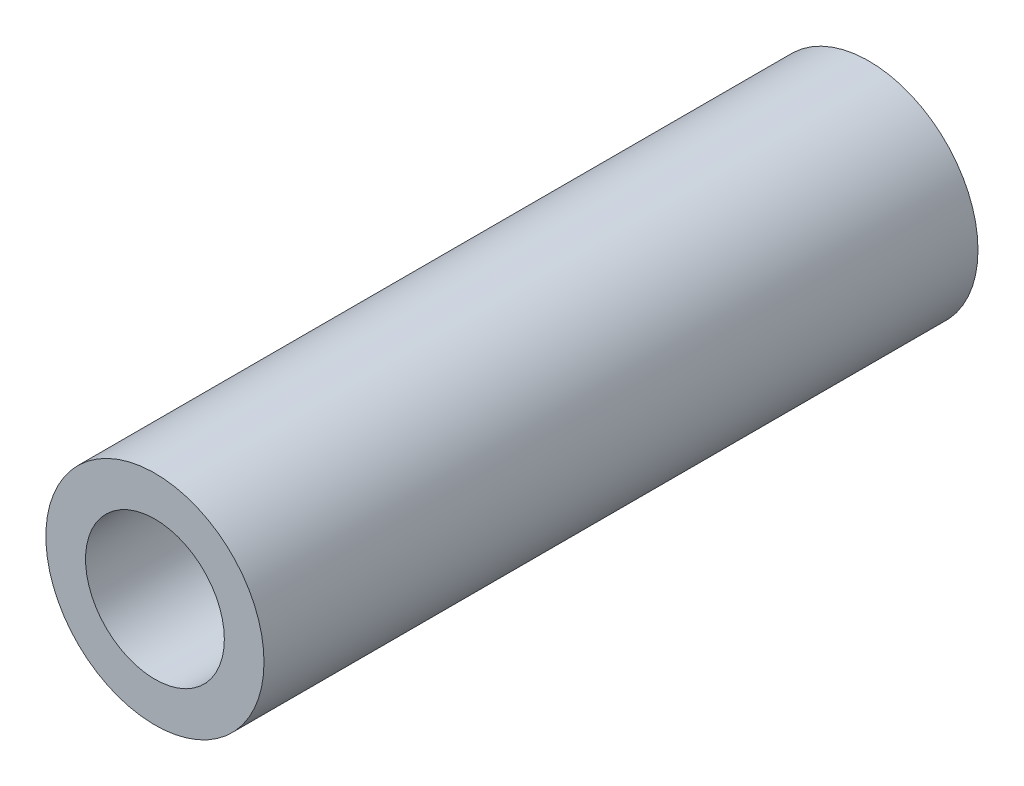
SolidWorks part; units mm, degrees
material "ABS"
ref_plane "前视基准面" through (0, 0, 0) normal (0, 0, 1) x (1, 0, 0)
ref_plane "上视基准面" through (0, 0, 0) normal (0, 1, 0) x (1, 0, 0)
ref_plane "右视基准面" through (0, 0, 0) normal (1, 0, 0) x (0, 0, -1)
sketch "草图1" plane through (0, 0, 0) normal (0, 0, 1) x (1, 0, 0)
  circle A0 centre (0, 0) radius 1.75
  circle A1 centre (0, 0) radius 2.75
  dimension "D1" = 3.5
  dimension "D2" = 5.5
extrude "凸台-拉伸1" add sketch "草图1" along normal blind 18
